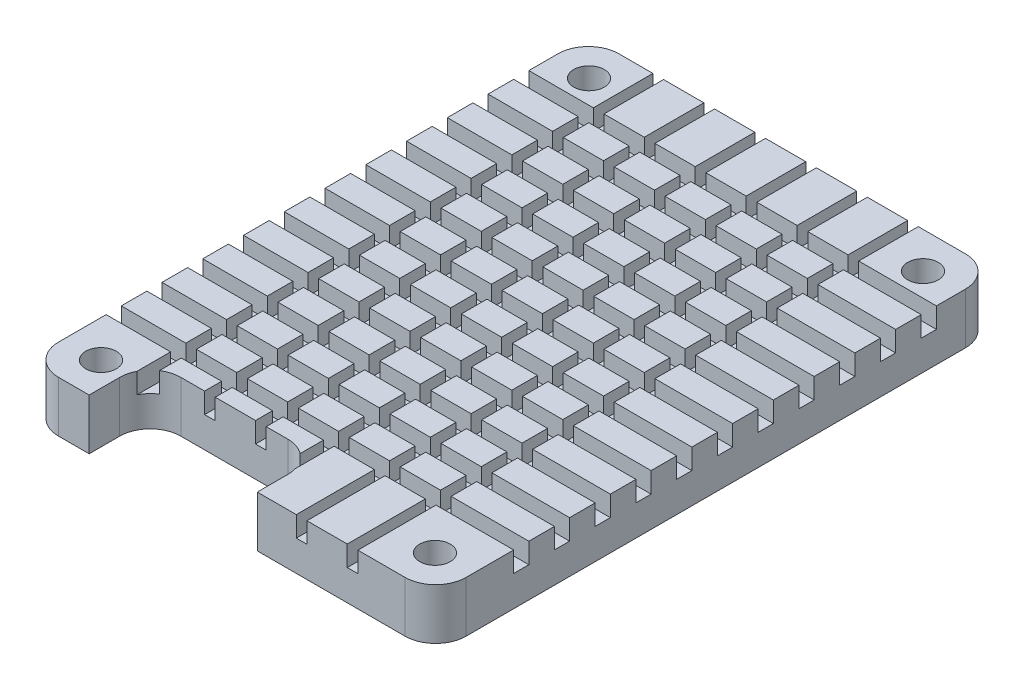
SolidWorks part; units mm, degrees
ref_plane "Front Plane" through (0, 0, 0) normal (0, 0, 1) x (1, 0, 0)
ref_plane "Top Plane" through (0, 0, 0) normal (0, 1, 0) x (1, 0, 0)
ref_plane "Right Plane" through (0, 0, 0) normal (1, 0, 0) x (0, 0, -1)
sketch "Sketch1" plane through (0, 0, 0) normal (0, 1, 0) x (1, 0, 0)
  line L1 (0, 0) -> (40, 0)
  line L2 (0, 0) -> (0, 55)
  line L3 (0, 55) -> (40, 55)
  line L4 (40, 0) -> (40, 55)
  dimension "D1" = 40
  dimension "D2" = 55
extrude "Boss-Extrude1" add sketch "Sketch1" along normal blind 5
sketch "Sketch2" plane through (0, 5, 0) normal (0, 1, 0) x (1, 0, 0)
  line L0 (0, 0) -> (40, 0) construction
  line L1 (6, 0) -> (22.5, 0)
  line L2 (6, 0) -> (6, 6)
  line L3 (6, 6) -> (22.5, 6)
  line L4 (22.5, 0) -> (22.5, 6)
  line L5 (0, 55) -> (0, 0) construction
  line L6 (20, 55) -> (20, 0) construction
  line L7 (3.6111, 51.4468) -> (36.3889, 51.4468) construction
  line L8 (3.6111, 51.4468) -> (3.6111, 3.5532) construction
  line L9 (3.6111, 3.5532) -> (36.3889, 3.5532) construction
  line L10 (36.3889, 51.4468) -> (36.3889, 3.5532) construction
  line L11 (40, 55) -> (0, 55) construction
  line L13 (0, 27.5) -> (40, 27.5) construction
  line L14 (40, 0) -> (40, 55) construction
  circle A0 centre (3.6111, 51.4468) radius 1.5
  circle A1 centre (36.3889, 51.4468) radius 1.5
  circle A2 centre (36.3889, 3.5532) radius 1.5
  circle A3 centre (3.6111, 3.5532) radius 1.5
  point P24 (2.3382, 52.0037)
  point P25 (3.1338, 4.4283)
  point P26 (3.5316, 3.3145)
  point P27 (3.6111, 3.5532)
  dimension "D4" = 3
  dimension "D1" = 6
  dimension "D2" = 6
  dimension "D3" = 16.5
extrude "Cut-Extrude1" cut sketch "Sketch2" against normal through all
fillet "Fillet1" radius 3 6 edges at (0, 2.5, -55) (40, 2.5, -55) (40, 2.5, 0) (0, 2.5, 0) (22.5, 2.5, -6) (6, 2.5, -6)
sketch "Sketch3" plane through (0, 5, 0) normal (0, 1, 0) x (1, 0, 0)
  line L0 (0, 52) -> (0, 3) construction
  line L1 (0, 49.1524) -> (40, 49.1524)
  line L2 (0, 49.1524) -> (0, 47.6631)
  line L3 (0, 47.6631) -> (40, 47.6631)
  line L4 (40, 49.1524) -> (40, 47.6631)
  line L5 (40, 3) -> (40, 52) construction
  line L6 (0, 43.6631) -> (40, 43.6631)
  line L7 (0, 45.1524) -> (40, 45.1524)
  line L8 (40, 45.1524) -> (40, 43.6631)
  line L9 (0, 45.1524) -> (0, 43.6631)
  line L10 (0, 39.6631) -> (40, 39.6631)
  line L11 (0, 41.1524) -> (40, 41.1524)
  line L12 (40, 41.1524) -> (40, 39.6631)
  line L13 (0, 41.1524) -> (0, 39.6631)
  line L14 (0, 35.6631) -> (40, 35.6631)
  line L15 (0, 37.1524) -> (40, 37.1524)
  line L16 (40, 37.1524) -> (40, 35.6631)
  line L17 (0, 37.1524) -> (0, 35.6631)
  line L18 (0, 31.6631) -> (40, 31.6631)
  line L19 (0, 33.1524) -> (40, 33.1524)
  line L20 (40, 33.1524) -> (40, 31.6631)
  line L21 (0, 33.1524) -> (0, 31.6631)
  line L22 (0, 27.6631) -> (40, 27.6631)
  line L23 (0, 29.1524) -> (40, 29.1524)
  line L24 (40, 29.1524) -> (40, 27.6631)
  line L25 (0, 29.1524) -> (0, 27.6631)
  line L26 (0, 23.6631) -> (40, 23.6631)
  line L27 (0, 25.1524) -> (40, 25.1524)
  line L28 (40, 25.1524) -> (40, 23.6631)
  line L29 (0, 25.1524) -> (0, 23.6631)
  line L30 (0, 19.6631) -> (40, 19.6631)
  line L31 (0, 21.1524) -> (40, 21.1524)
  line L32 (40, 21.1524) -> (40, 19.6631)
  line L33 (0, 21.1524) -> (0, 19.6631)
  line L34 (0, 15.6631) -> (40, 15.6631)
  line L35 (0, 17.1524) -> (40, 17.1524)
  line L36 (40, 17.1524) -> (40, 15.6631)
  line L37 (0, 17.1524) -> (0, 15.6631)
  line L38 (0, 11.6631) -> (40, 11.6631)
  line L39 (0, 13.1524) -> (40, 13.1524)
  line L40 (40, 13.1524) -> (40, 11.6631)
  line L41 (0, 13.1524) -> (0, 11.6631)
  line L42 (0, 7.6631) -> (40, 7.6631)
  line L43 (0, 9.1524) -> (40, 9.1524)
  line L44 (40, 9.1524) -> (40, 7.6631)
  line L45 (0, 9.1524) -> (0, 7.6631)
  line L46 (37, 55) -> (3, 55) construction
  line L47 (6.3305, 55) -> (7.3744, 55)
  line L48 (6.3305, 55) -> (6.3305, 0)
  line L49 (6.3305, 0) -> (7.3744, 0)
  line L50 (7.3744, 55) -> (7.3744, 0)
  line L51 (11.3305, 55) -> (11.3305, 0)
  line L52 (11.3305, 55) -> (12.3744, 55)
  line L53 (12.3744, 55) -> (12.3744, 0)
  line L54 (11.3305, 0) -> (12.3744, 0)
  line L55 (16.3305, 55) -> (16.3305, 0)
  line L56 (16.3305, 55) -> (17.3744, 55)
  line L57 (17.3744, 55) -> (17.3744, 0)
  line L58 (16.3305, 0) -> (17.3744, 0)
  line L59 (21.3305, 55) -> (21.3305, 0)
  line L60 (21.3305, 55) -> (22.3744, 55)
  line L61 (22.3744, 55) -> (22.3744, 0)
  line L62 (21.3305, 0) -> (22.3744, 0)
  line L63 (26.3305, 55) -> (26.3305, 0)
  line L64 (26.3305, 55) -> (27.3744, 55)
  line L65 (27.3744, 55) -> (27.3744, 0)
  line L66 (26.3305, 0) -> (27.3744, 0)
  line L67 (31.3305, 55) -> (31.3305, 0)
  line L68 (31.3305, 55) -> (32.3744, 55)
  line L69 (32.3744, 55) -> (32.3744, 0)
  line L70 (31.3305, 0) -> (32.3744, 0)
  dimension "D1" = 11
  dimension "D2" = 6
extrude "Cut-Extrude2" cut sketch "Sketch3" against normal blind 2 contours L42 L44 L43 L45 | L38 L40 L39 L41 | L34 L36 L35 L37 | L30 L32 L31 L33 | L53 L54 L51 L52 | L50 L49 L48 L47 | L57 L58 L55 L56 | L61 L62 L59 L60 | L65 L66 L63 L64 | L69 L70 L67 L68 | L26 L28 L27 L29 | L22 L24 L23 L25 | L18 L20 L19 L21 | L14 L16 L15 L17 | L10 L12 L11 L13 | L6 L8 L7 L9 | L1 L4 L3 L2
